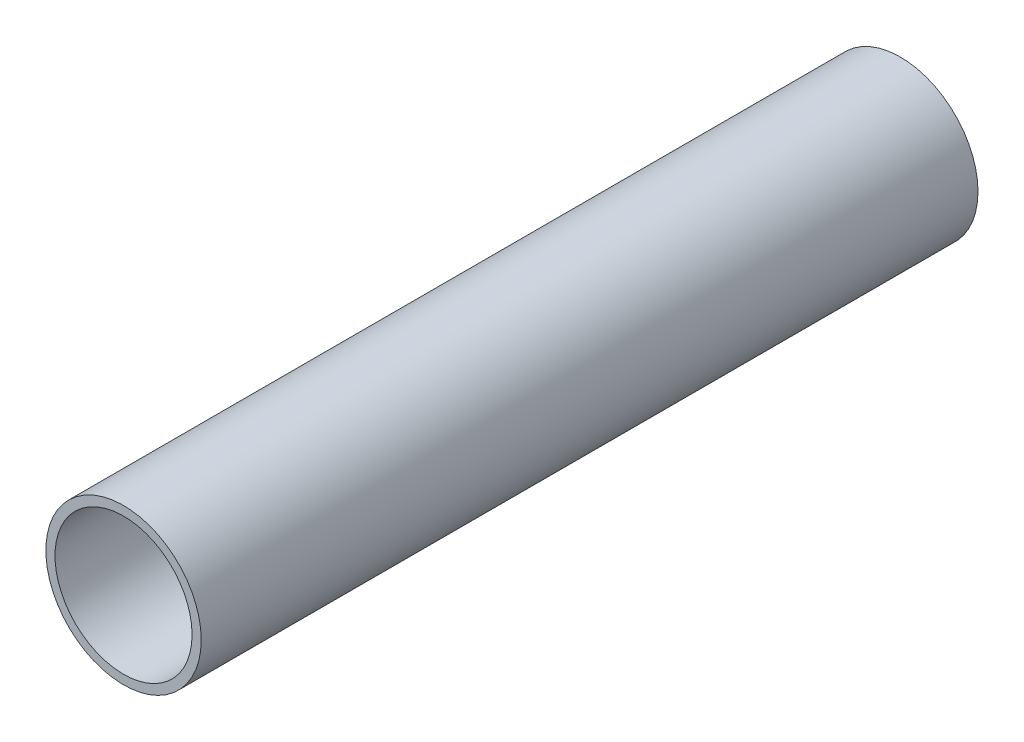
SolidWorks part; units mm, degrees
ref_plane "Front Plane" through (0, 0, 0) normal (0, 0, 1) x (1, 0, 0)
ref_plane "Top Plane" through (0, 0, 0) normal (0, 1, 0) x (1, 0, 0)
ref_plane "Right Plane" through (0, 0, 0) normal (1, 0, 0) x (0, 0, -1)
sketch "Sketch1" plane through (0, 0, 0) normal (0, 0, 1) x (1, 0, 0)
  circle A0 centre (0, 0) radius 15
  circle A1 centre (0, 0) radius 17
  dimension "D1" = 30
  dimension "D2" = 2
extrude "Boss-Extrude1" add sketch "Sketch1" along normal mid plane 170 contours A1 A0
